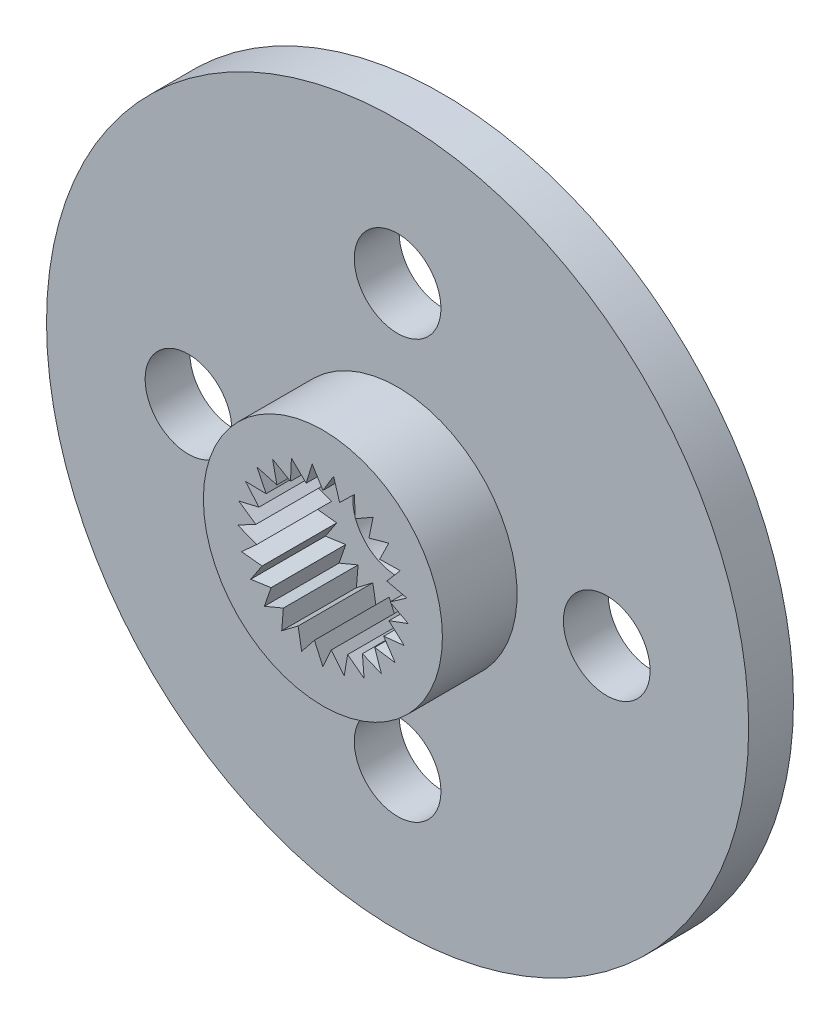
SolidWorks part; units mm, degrees
ref_plane "前视基准面" through (0, 0, 0) normal (0, 0, 1) x (1, 0, 0)
ref_plane "上视基准面" through (0, 0, 0) normal (0, 1, 0) x (1, 0, 0)
ref_plane "右视基准面" through (0, 0, 0) normal (1, 0, 0) x (0, 0, -1)
sketch "草图1" plane through (0, 0, 0) normal (0, 0, 1) x (1, 0, 0)
  line L0 (0, 0) -> (0, 2.25) construction
  line L1 (0, 0) -> (0.5596, 2.1793) construction
  line L2 (0, 2.25) -> (0.5596, 2.1793) construction
  line L3 (0, 2.25) -> (0.3587, 2.8394)
  line L4 (0.3587, 2.8394) -> (0.5596, 2.1793)
  line L5 (1.0536, 2.661) -> (1.0839, 1.9717)
  line L6 (0.5596, 2.1793) -> (1.0536, 2.661)
  line L7 (1.6822, 2.3154) -> (1.5402, 1.6402)
  line L8 (1.0839, 1.9717) -> (1.6822, 2.3154)
  line L9 (2.2052, 1.8243) -> (1.8997, 1.2056)
  line L10 (1.5402, 1.6402) -> (2.2052, 1.8243)
  line L11 (2.5896, 1.2186) -> (2.1399, 0.6953)
  line L12 (1.8997, 1.2056) -> (2.5896, 1.2186)
  line L13 (2.8113, 0.5363) -> (2.2456, 0.1413)
  line L14 (2.1399, 0.6953) -> (2.8113, 0.5363)
  line L15 (2.8564, -0.1797) -> (2.2101, -0.4216)
  line L16 (2.2456, 0.1413) -> (2.8564, -0.1797)
  line L17 (2.7219, -0.8844) -> (2.0359, -0.958)
  line L18 (2.2101, -0.4216) -> (2.7219, -0.8844)
  line L19 (2.4165, -1.5335) -> (1.7337, -1.4342)
  line L20 (2.0359, -0.958) -> (2.4165, -1.5335)
  line L21 (1.9592, -2.0863) -> (1.3225, -1.8203)
  line L22 (1.7337, -1.4342) -> (1.9592, -2.0863)
  line L23 (1.3788, -2.508) -> (0.8283, -2.092)
  line L24 (1.3225, -1.8203) -> (1.3788, -2.508)
  line L25 (0.7118, -2.7721) -> (0.282, -2.2323)
  line L26 (0.8283, -2.092) -> (0.7118, -2.7721)
  line L27 (0, -2.862) -> (-0.282, -2.2323)
  line L28 (0.282, -2.2323) -> (0, -2.862)
  line L29 (-0.7118, -2.7721) -> (-0.8283, -2.092)
  line L30 (-0.282, -2.2323) -> (-0.7118, -2.7721)
  line L31 (-1.3788, -2.508) -> (-1.3225, -1.8203)
  line L32 (-0.8283, -2.092) -> (-1.3788, -2.508)
  line L33 (-1.9592, -2.0863) -> (-1.7337, -1.4342)
  line L34 (-1.3225, -1.8203) -> (-1.9592, -2.0863)
  line L35 (-2.4165, -1.5335) -> (-2.0359, -0.958)
  line L36 (-1.7337, -1.4342) -> (-2.4165, -1.5335)
  line L37 (-2.7219, -0.8844) -> (-2.2101, -0.4216)
  line L38 (-2.0359, -0.958) -> (-2.7219, -0.8844)
  line L39 (-2.8564, -0.1797) -> (-2.2456, 0.1413)
  line L40 (-2.2101, -0.4216) -> (-2.8564, -0.1797)
  line L41 (-2.8113, 0.5363) -> (-2.1399, 0.6953)
  line L42 (-2.2456, 0.1413) -> (-2.8113, 0.5363)
  line L43 (-2.5896, 1.2186) -> (-1.8997, 1.2056)
  line L44 (-2.1399, 0.6953) -> (-2.5896, 1.2186)
  line L45 (-2.2052, 1.8243) -> (-1.5402, 1.6402)
  line L46 (-1.8997, 1.2056) -> (-2.2052, 1.8243)
  line L47 (-1.6822, 2.3154) -> (-1.0839, 1.9717)
  line L48 (-1.5402, 1.6402) -> (-1.6822, 2.3154)
  line L49 (-1.0536, 2.661) -> (-0.5596, 2.1793)
  line L50 (-1.0839, 1.9717) -> (-1.0536, 2.661)
  line L51 (-0.3587, 2.8394) -> (0, 2.25)
  line L52 (-0.5596, 2.1793) -> (-0.3587, 2.8394)
  circle A0 centre (0, 0) radius 2.25 construction
  circle A1 centre (0, 0) radius 4
  point P4 (0.2798, 2.2147)
  point P82 (0, 0)
  dimension "D2" = 4.5
  dimension "D7" = 8
  dimension "D1" = 14.4
  dimension "D3" = 0.564
  dimension "D4" = 0.69
  dimension "D5" = 0.69
  dimension "D6" = 25
extrude "凸台-拉伸1" add sketch "草图1" along normal blind 2.5
sketch "草图2" plane through (0, 0, 0) normal (0, 0, -1) x (-1, 0, 0)
  circle A0 centre (0, 0) radius 11.75
  circle A1 centre (-7, 0) radius 1.45
  circle A2 centre (0, 0) radius 7 construction
  circle A3 centre (0, 7) radius 1.45
  circle A4 centre (7, 0) radius 1.45
  circle A5 centre (0, -7) radius 1.45
  circle A6 centre (0, 0) radius 1.5
  point P15 (0, 0)
  dimension "D1" = 23.5
  dimension "D2" = 2.9
  dimension "D5" = 3
  dimension "D3" = 7
  dimension "D4" = 4
extrude "凸台-拉伸2" add sketch "草图2" along normal blind 1.5
